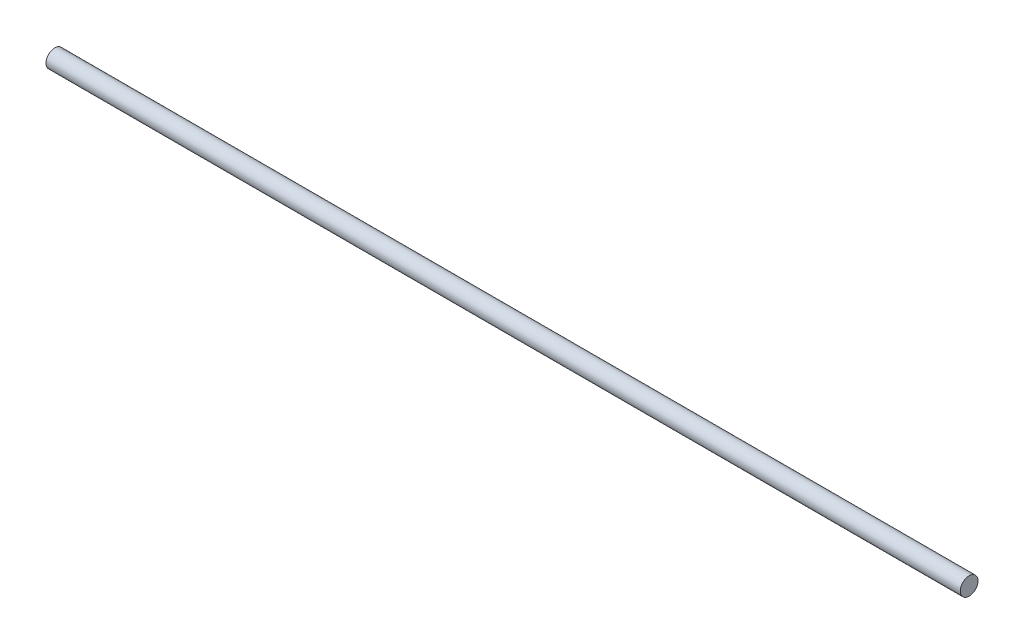
SolidWorks part; units mm, degrees
material "Plain Carbon Steel"
ref_plane "Front Plane" through (0, 0, 0) normal (0, 0, 1) x (1, 0, 0)
ref_plane "Top Plane" through (0, 0, 0) normal (0, 1, 0) x (1, 0, 0)
ref_plane "Right Plane" through (0, 0, 0) normal (1, 0, 0) x (0, 0, -1)
sketch "Sketch1" plane through (0, 0, 0) normal (1, 0, 0) x (0, 0, -1)
  circle A0 centre (0, 0) radius 6
  dimension "D1" = 12
extrude "Boss-Extrude1" add sketch "Sketch1" along normal mid plane 620
